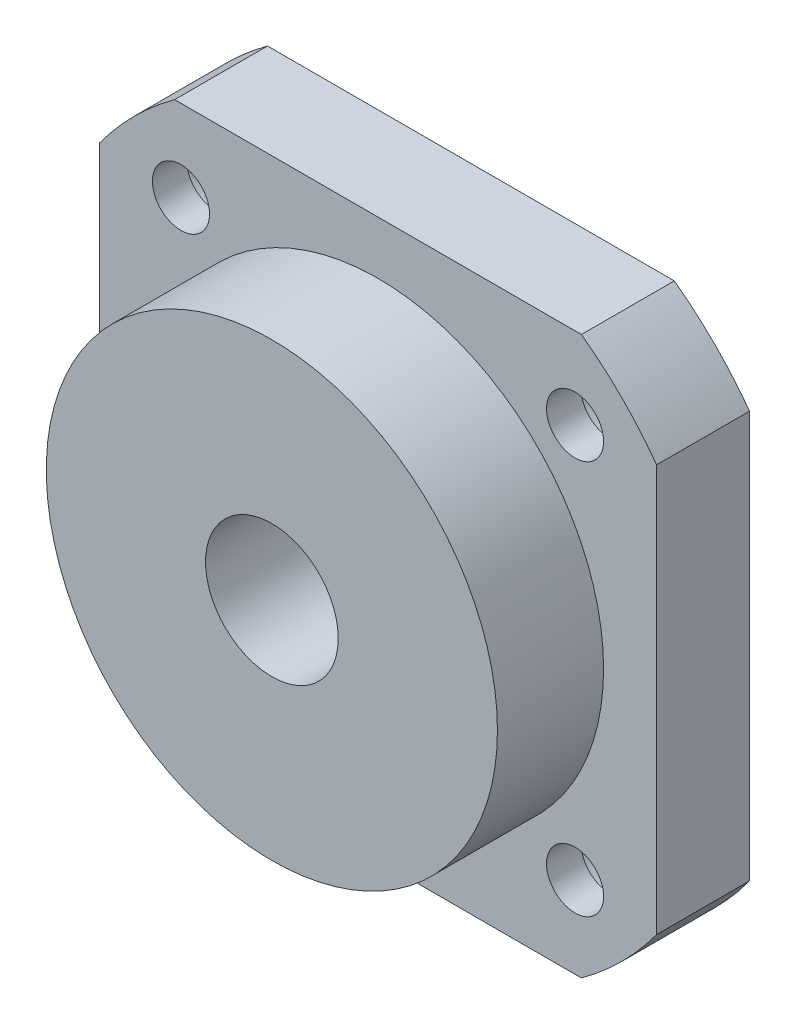
SolidWorks part; units mm, degrees
ref_plane "Front Plane" through (0, 0, 0) normal (0, 0, 1) x (1, 0, 0)
ref_plane "Top Plane" through (0, 0, 0) normal (0, 1, 0) x (1, 0, 0)
ref_plane "Right Plane" through (0, 0, 0) normal (1, 0, 0) x (0, 0, -1)
sketch "Sketch1" plane through (0, 0, 0) normal (0, 0, 1) x (1, 0, 0)
  line L1 (15.3297, -21) -> (-15.3297, -21)
  line L2 (21, -15.3297) -> (21, 15.3297)
  line L3 (15.3297, 21) -> (-15.3297, 21)
  line L4 (-21, -15.3297) -> (-21, 15.3297)
  line L5 (18.3848, -18.3848) -> (-21, 21) construction
  line L6 (18.3848, 18.3848) -> (-18.3848, -18.3848) construction
  arc A0 (-15.3297, 21) -> (-21, 15.3297) centre (0, 0) ccw
  arc A1 (-21, -15.3297) -> (-15.3297, -21) centre (0, 0) ccw
  arc A2 (15.3297, -21) -> (21, -15.3297) centre (0, 0) ccw
  arc A3 (21, 15.3297) -> (15.3297, 21) centre (0, 0) ccw
  circle A4 centre (0, 0) radius 5
  point P0 (0, 0)
  point P3 (-14.8492, 14.8492)
  point P19 (14.8492, 14.8492)
  point P20 (14.8492, -14.8492)
  point P21 (-14.8492, -14.8492)
  point P22 (0, 0)
  dimension "D3" = 52
  dimension "D4" = 10
  dimension "D1" = 21
  dimension "D2" = 4
extrude "Boss-Extrude1" add sketch "Sketch1" along normal blind 15
sketch "Sketch2" plane through (0, 0, 15) normal (0, 0, 1) x (1, 0, 0)
  circle A0 centre (0, 0) radius 17
  dimension "D1" = 34
extrude "Cut-Extrude-Thin1" cut sketch "Sketch2" against normal blind 8 thin
sketch "Sketch6" plane through (0, 0, 0) normal (0, 0, -1) x (-1, 0, 0)
  line L0 (0, 0) -> (-21, 0) construction
  line L1 (-21, -15.3297) -> (-21, 15.3297) construction
  line L2 (0, 0) -> (-18.3848, 18.3848) construction
  arc A0 (-15.3297, 21) -> (-21, 15.3297) centre (0, 0) ccw construction
  point P5 (-14.8492, 14.8492)
  point P13 (14.8492, 14.8492)
  point P14 (14.8492, -14.8492)
  point P15 (-14.8492, -14.8492)
  point P16 (0, 0)
  dimension "D1" = 21
  dimension "D2" = 4
hole_wizard "CBORE for M4 Hex Socket Head Cap Screw1" positions "3DSketch4" profile "Sketch8" counterbore size "M4" standard "ISO"
sketch3d "3DSketch4"
  point P0 (-14.8492, 14.8492, 0)
sketch "Sketch8" plane through (-14.8492, 14.8492, 0) normal (1, 0, 0) x (0, 1, 0)
  line L0 (0, 0) -> (0, 9.7919)
  line L1 (0, 9.7919) -> (2.15, 8.5)
  line L2 (2.15, 8.5) -> (2.15, 4.4)
  line L3 (2.15, 4.4) -> (4, 4.4)
  line L4 (4, 4.4) -> (4, 0)
  line L5 (4, 0) -> (0, 0)
  line L10 (0, 9.7919) -> (-2.15, 8.5) construction
  line L11 (0, -6.35) -> (0, 107.95) construction
  dimension "Hole Dia." = 4.3
  dimension "Hole Depth" = 8.5
  dimension "C'Bore Dia." = 8
  dimension "C'Bore Depth" = 4.4
  dimension "Drill Angle" = 118
hole_wizard "CBORE for M4 Hex Socket Head Cap Screw2" positions "3DSketch6" profile "Sketch10" counterbore size "M4" standard "ISO"
sketch3d "3DSketch6"
  point P0 (14.8492, 14.8492, 0)
sketch "Sketch10" plane through (14.8492, 14.8492, 0) normal (1, 0, 0) x (0, 1, 0)
  line L0 (0, 0) -> (0, 9.7919)
  line L1 (0, 9.7919) -> (2.15, 8.5)
  line L2 (2.15, 8.5) -> (2.15, 4.4)
  line L3 (2.15, 4.4) -> (4, 4.4)
  line L4 (4, 4.4) -> (4, 0)
  line L5 (4, 0) -> (0, 0)
  line L10 (0, 9.7919) -> (-2.15, 8.5) construction
  line L11 (0, -6.35) -> (0, 107.95) construction
  dimension "Hole Dia." = 4.3
  dimension "Hole Depth" = 8.5
  dimension "C'Bore Dia." = 8
  dimension "C'Bore Depth" = 4.4
  dimension "Drill Angle" = 118
hole_wizard "CBORE for M4 Hex Socket Head Cap Screw3" positions "3DSketch7" profile "Sketch11" counterbore size "M4" standard "ISO"
sketch3d "3DSketch7"
  point P0 (14.8492, -14.8492, 0)
sketch "Sketch11" plane through (14.8492, -14.8492, 0) normal (1, 0, 0) x (0, 1, 0)
  line L0 (0, 0) -> (0, 9.7919)
  line L1 (0, 9.7919) -> (2.15, 8.5)
  line L2 (2.15, 8.5) -> (2.15, 4.4)
  line L3 (2.15, 4.4) -> (4, 4.4)
  line L4 (4, 4.4) -> (4, 0)
  line L5 (4, 0) -> (0, 0)
  line L10 (0, 9.7919) -> (-2.15, 8.5) construction
  line L11 (0, -6.35) -> (0, 107.95) construction
  dimension "Hole Dia." = 4.3
  dimension "Hole Depth" = 8.5
  dimension "C'Bore Dia." = 8
  dimension "C'Bore Depth" = 4.4
  dimension "Drill Angle" = 118
hole_wizard "CBORE for M4 Hex Socket Head Cap Screw4" positions "3DSketch8" profile "Sketch12" counterbore size "M4" standard "ISO"
sketch3d "3DSketch8"
  point P0 (-14.8492, -14.8492, 0)
sketch "Sketch12" plane through (-14.8492, -14.8492, 0) normal (1, 0, 0) x (0, 1, 0)
  line L0 (0, 0) -> (0, 9.7919)
  line L1 (0, 9.7919) -> (2.15, 8.5)
  line L2 (2.15, 8.5) -> (2.15, 4.4)
  line L3 (2.15, 4.4) -> (4, 4.4)
  line L4 (4, 4.4) -> (4, 0)
  line L5 (4, 0) -> (0, 0)
  line L10 (0, 9.7919) -> (-2.15, 8.5) construction
  line L11 (0, -6.35) -> (0, 107.95) construction
  dimension "Hole Dia." = 4.3
  dimension "Hole Depth" = 8.5
  dimension "C'Bore Dia." = 8
  dimension "C'Bore Depth" = 4.4
  dimension "Drill Angle" = 118
